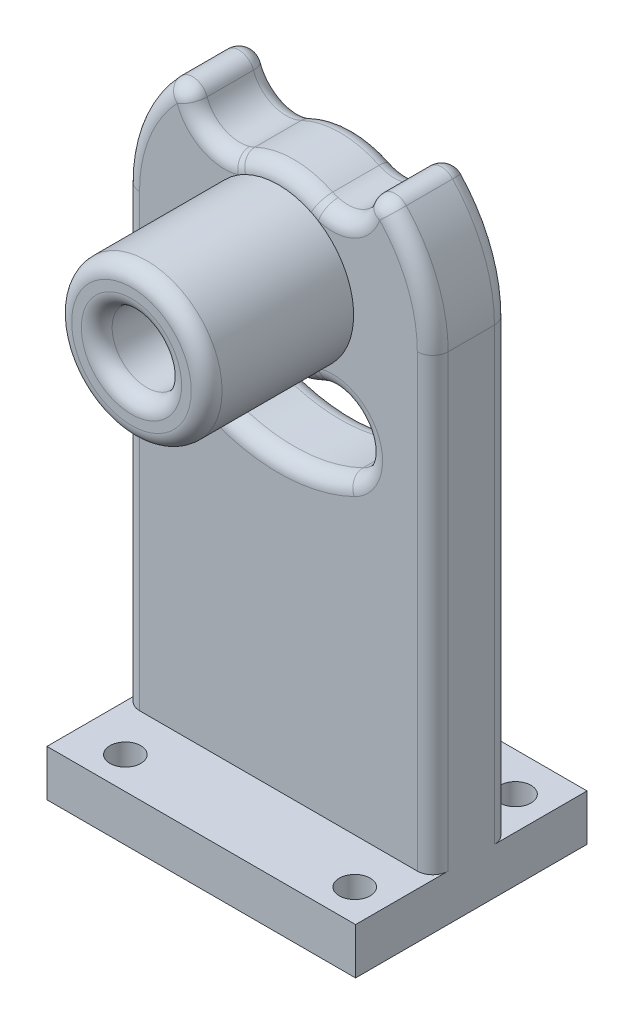
SolidWorks part; units mm, degrees
material "ABS"
ref_plane "Plan de face" through (0, 0, 0) normal (0, 0, 1) x (1, 0, 0)
ref_plane "Plan de dessus" through (0, 0, 0) normal (0, 1, 0) x (1, 0, 0)
ref_plane "Plan de droite" through (0, 0, 0) normal (1, 0, 0) x (0, 0, -1)
sketch "Esquisse1" plane through (0, 0, 0) normal (0, 0, 1) x (1, 0, 0)
  line L0 (-10, -32.1469) -> (-10, 0)
  line L1 (10, 0) -> (10, -32.1469)
  line L2 (10, -32.1469) -> (-10, -32.1469)
  arc A0 (-10, 0) -> (10, 0) centre (0, 0) cw
  dimension "D2" = 32.1469
  dimension "D1" = 20
extrude "Boss.-Extru.1" add sketch "Esquisse1" along normal blind 5
sketch "Esquisse2" plane through (0, 0, 5) normal (0, 0, 1) x (1, 0, 0)
  circle A0 centre (0, 0) radius 4.875
  dimension "D1" = 9.75
sketch "Esquisse3" plane through (0, 0, 5) normal (0, 0, 1) x (1, 0, 0)
  line L0 (10, -32.1469) -> (10, 0) construction
  line L1 (-10, -32.1469) -> (10, -32.1469)
  line L2 (-10, -32.1469) -> (-10, -29.1469)
  line L3 (-10, -29.1469) -> (10, -29.1469)
  line L4 (10, -32.1469) -> (10, -29.1469)
  dimension "D1" = 3
extrude "Boss.-Extru.2" add sketch "Esquisse3" along normal blind 5 and the other way blind 10
sketch "Esquisse4" plane through (0, -29.1469, 0) normal (0, 1, 0) x (1, 0, 0)
  line L0 (-10, 5) -> (-10, 0) construction
  line L1 (10, 5) -> (-10, 5) construction
  circle A0 centre (-7, -7.9207) radius 1
  circle A1 centre (7.8654, -7.9207) radius 1
  circle A2 centre (7.8654, 2.5) radius 1
  circle A4 centre (-7, 2.5) radius 1
  dimension "D1" = 2
  dimension "D2" = 3
  dimension "D3" = 2.5
extrude "Enlèv. mat.-Extru.2" cut sketch "Esquisse4" against normal blind 5
extrude "Boss.-Extru.3" add sketch "Esquisse2" along normal blind 9.525
sketch "Esquisse5" plane through (0, 0, 5) normal (0, 0, 1) x (1, 0, 0)
  line L0 (0, 0) -> (0, -8.05) construction
  arc A0 (-3.5, -7.2493) -> (3.5, -7.2493) centre (0, 0) ccw construction
  arc A1 (-4.4783, -9.2755) -> (4.4783, -9.2755) centre (0, 0) ccw
  arc A2 (-2.5217, -5.2231) -> (2.5217, -5.2231) centre (0, 0) ccw
  arc A3 (-2.5217, -5.2231) -> (-4.4783, -9.2755) centre (-3.5, -7.2493) ccw
  arc A4 (4.4783, -9.2755) -> (2.5217, -5.2231) centre (3.5, -7.2493) ccw
  point P4 (0, -8.05)
  dimension "D1" = 4.5
  dimension "D2" = 8.05
  dimension "D3" = 7
extrude "Enlèv. mat.-Extru.3" cut sketch "Esquisse5" against normal through all
mirror "Symétrie1" about plane through (0, 0, 0) normal (0, 1, 0) of "Enlèv. mat.-Extru.3"
fillet "Congé1" radius 1 23 edges at (0, -10.3, 5) (-5.5262, -6.271, 5) (0, -5.8, 0) (-5.5262, -6.271, 0) (0, -10.3, 0) (10, -14.5734, 0) (-10, -14.5734, 0) (10, -14.5734, 5) (-10, -14.5734, 5) (5.5262, -6.271, 5) (5.5262, -6.271, 0) (-8.7859, 4.7759, 0) (8.7859, 4.7759, 0) (-8.7859, 4.7759, 5) (8.7859, 4.7759, 5) (4.875, 0, 14.525) (-5.1556, 5.7256, 0) (5.1556, 5.7256, 0) (5.1556, 5.7256, 5) (-5.1556, 5.7256, 5) (0, 5.8, 0) (5.4382, 8.392, 2.5) (-5.4382, 8.392, 2.5)
sketch "Esquisse6" plane through (0, 0, 14.525) normal (0, 0, 1) x (1, 0, 0)
  circle A0 centre (0, 0) radius 2.25
  dimension "D1" = 4.5
extrude "Enlèv. mat.-Extru.4" cut sketch "Esquisse6" against normal through all contours A0
fillet "Congé2" radius 1 2 edges at (2.25, 0, 14.525) (-2.25, 0, 0)
